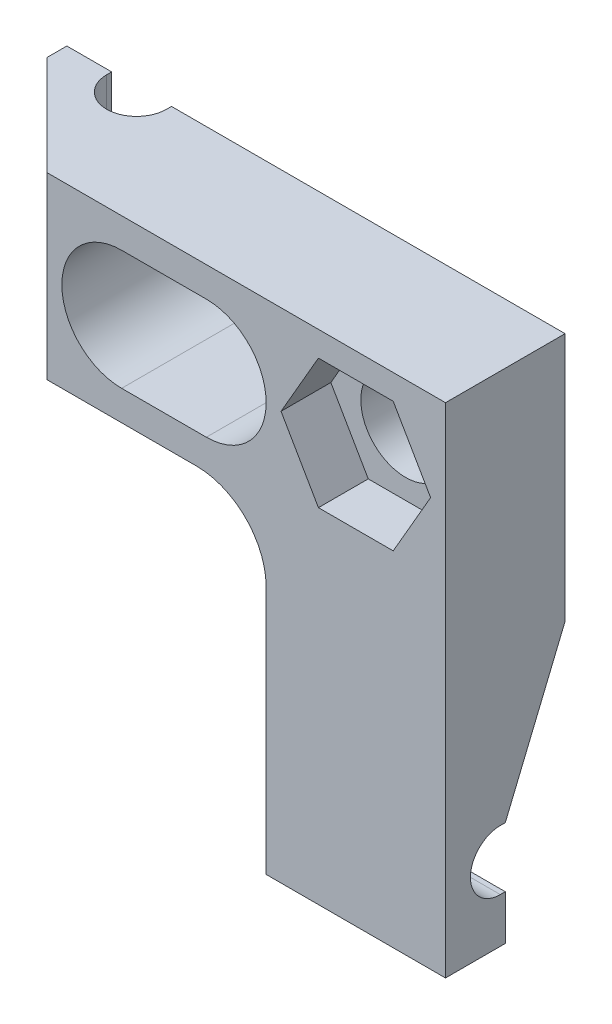
SolidWorks part; units mm, degrees
ref_plane "xy" through (0, 0, 0) normal (0, 0, 1) x (1, 0, 0)
ref_plane "xz" through (0, 0, 0) normal (0, 1, 0) x (1, 0, 0)
ref_plane "yz" through (0, 0, 0) normal (1, 0, 0) x (0, 0, -1)
sketch "Skizze1" plane through (0, 0, 0) normal (0, 0, 1) x (1, 0, 0)
  line L0 (0, 0) -> (-27.5, -27.5) construction
  line L1 (12.5, 54.5) -> (54.5, 12.5) construction
  line L2 (12.5, 54.5) -> (54.5, 54.5) construction
  line L3 (12.5, 54.5) -> (12.5, 12.5) construction
  line L4 (12.5, 12.5) -> (54.5, 12.5) construction
  line L5 (-7.5, -7.5) -> (-27.5, -7.5) construction
  line L6 (-7.5, -7.5) -> (-7.5, -27.5) construction
  line L7 (-7.5, -27.5) -> (-27.5, -27.5) construction
  line L8 (-27.5, -7.5) -> (-27.5, -27.5) construction
  line L9 (-27.5, -7.5) -> (-22.5, -7.5) construction
  line L10 (-27.5, -7.5) -> (-27.5, 7.5) construction
  line L11 (-27.5, 7.5) -> (-22.5, 7.5) construction
  line L12 (-22.5, -7.5) -> (-22.5, 7.5) construction
  line L13 (-27.5, 3) -> (55.808, 3) construction
  line L14 (-27.5, 3) -> (-27.5, -3) construction
  line L15 (-27.5, -3) -> (55.808, -3) construction
  line L16 (55.808, 3) -> (55.808, -3) construction
  line L17 (-7.5, -7.5) -> (12.5, -7.5) construction
  line L18 (12.5, -7.5) -> (12.5, -27.5) construction
  line L19 (12.5, -27.5) -> (-7.5, -27.5) construction
  line L20 (12.5, -17.5) -> (14.5, -17.5) construction
  line L21 (14.5, -10) -> (19.5, -10) construction
  line L22 (14.5, -10) -> (14.5, -25) construction
  line L23 (14.5, -25) -> (19.5, -25) construction
  line L24 (19.5, -10) -> (19.5, -25) construction
  line L25 (54.5, 54.5) -> (54.5, 12.5) construction
  line L27 (-3, -38.6322) -> (3, -38.6322) construction
  line L28 (-3, -38.6322) -> (-3, 55.6456) construction
  line L29 (-3, 55.6456) -> (3, 55.6456) construction
  line L30 (3, -38.6322) -> (3, 55.6456) construction
  line L31 (39.5, 36.9641) -> (33.5, 40.4282)
  line L32 (33.5, 40.4282) -> (27.5, 36.9641)
  line L33 (27.5, 36.9641) -> (27.5, 30.0359)
  line L34 (27.5, 30.0359) -> (33.5, 26.5718)
  line L35 (33.5, 26.5718) -> (39.5, 30.0359)
  line L36 (39.5, 30.0359) -> (39.5, 36.9641)
  circle A0 centre (33.5, 33.5) radius 6 construction
  point P18 (-27.5, 0)
  point P28 (17, -10)
  point P31 (33.5, 33.5)
  dimension "D1" = 42
  dimension "D2" = 20
  dimension "D3" = 5
  dimension "D4" = 15
  dimension "D5" = 6
  dimension "D6" = 2
  dimension "D7" = 20
  dimension "D8" = 20
  dimension "D9" = 4.5
  dimension "D10" = 12
sketch "Skizze2" plane through (0, 0, 0) normal (0, 0, 1) x (1, 0, 0)
  line L0 (-7.5, 42.5) -> (-7.5, 24.5)
  line L1 (-7.5, 24.5) -> (17.5, 24.5)
  line L2 (24.5, 17.5) -> (24.5, -7.5)
  line L3 (24.5, -7.5) -> (42.5, -7.5)
  line L4 (42.5, -7.5) -> (42.5, 42.5)
  line L5 (-7.5, 42.5) -> (42.5, 42.5)
  line L6 (-7.5, -7.5) -> (-7.5, -27.5) construction
  arc A0 (17.5, 24.5) -> (24.5, 17.5) centre (17.5, 17.5) cw
  circle A1 centre (33.5, 33.5) radius 4.5
  point P12 (33.5, -7.5)
  point P14 (-7.5, 33.5)
  dimension "D3" = 9
  dimension "D1" = 18
  dimension "D2" = 25
extrude "Aufsatz-Linear austragen1" add sketch "Skizze2" along normal blind 12
sketch "Skizze5" plane through (0, 0, 12) normal (0, 0, 1) x (1, 0, 0)
  line L0 (39.5, 36.9641) -> (39.1292, 36.75) construction
  line L1 (41.0056, 33.5) -> (37.2528, 40)
  line L2 (37.2528, 40) -> (29.7472, 40)
  line L3 (29.7472, 40) -> (25.9944, 33.5)
  line L4 (25.9944, 33.5) -> (29.7472, 27)
  line L5 (29.7472, 27) -> (37.2528, 27)
  line L6 (37.2528, 27) -> (41.0056, 33.5)
  circle A0 centre (33.5, 33.5) radius 6.5 construction
  dimension "D1" = 13
extrude "Schnitt-Linear austragen6" cut sketch "Skizze5" against normal blind 5
sketch "Skizze3" plane through (0, 0, 0) normal (0, 1, 0) x (1, 0, 0)
  line L0 (0, 4.577) -> (0, -0.5) construction
  line L1 (3, 4.577) -> (3, -0.5)
  line L2 (-3, 4.577) -> (-3, -0.5)
  line L3 (-45.8194, 0) -> (45.8194, 0) construction
  arc A0 (3, 4.577) -> (-3, 4.577) centre (0, 4.577) ccw
  arc A1 (-3, -0.5) -> (3, -0.5) centre (0, -0.5) ccw
  point P2 (0, 2.0385)
  dimension "D2" = 3
  dimension "D1" = 0.5
extrude "Schnitt-Linear austragen1" cut sketch "Skizze3" along normal through all
sketch "Skizze4" plane through (0, 0, 0) normal (1, 0, 0) x (0, 0, -1)
  line L0 (-0.5, 0) -> (-6.5, 0) construction
  line L1 (-0.5, -3) -> (-6.5, -3)
  line L2 (-0.5, 3) -> (-6.5, 3)
  line L3 (4.577, 0) -> (-0.5, 0) construction
  arc A0 (-0.5, -3) -> (-0.5, 3) centre (-0.5, 0) ccw
  arc A1 (-6.5, 3) -> (-6.5, -3) centre (-6.5, 0) ccw
  point P2 (-3.5, 0)
  dimension "D1" = 3
  dimension "D2" = 6
  dimension "D3" = 6
extrude "Schnitt-Linear austragen5" cut sketch "Skizze4" along normal through all
sketch "Skizze6" plane through (0, 0, 0) normal (0, 0, -1) x (-1, 0, 0)
  line L1 (-42.5, -7.5) -> (-24.5, -7.5)
  line L2 (-42.5, -7.5) -> (-42.5, 17.5)
  line L3 (-42.5, 17.5) -> (-24.5, 17.5)
  line L4 (-24.5, -7.5) -> (-24.5, 17.5)
extrude "Schnitt-Linear austragen7" cut sketch "Skizze6" against normal blind 6
sketch "Skizze7" plane through (42.5, 0, 0) normal (1, 0, 0) x (0, 0, -1)
  line L0 (-6, 3) -> (-6, 17.5)
  line L1 (-6, 17.5) -> (0, 17.5)
  line L2 (0, 17.5) -> (-6, 3)
extrude "Aufsatz-Linear austragen2" add sketch "Skizze7" against normal blind 3
sketch "Skizze8" plane through (24.5, 0, 0) normal (-1, 0, 0) x (0, 0, 1)
  line L0 (6, 3) -> (6, 17.5)
  line L1 (6, 17.5) -> (0, 17.5)
  line L2 (0, 17.5) -> (6, 3)
extrude "Aufsatz-Linear austragen3" add sketch "Skizze8" against normal blind 3
sketch "Skizze9" plane through (0, 0, 0) normal (0, 0, -1) x (-1, 0, 0)
  line L0 (-18.5, 33.5) -> (-10, 33.5) construction
  line L1 (-18.5, 39.5) -> (-10, 39.5)
  line L2 (-18.5, 27.5) -> (-10, 27.5)
  line L3 (-3, -38.6322) -> (-3, 55.6456) construction
  line L4 (-27.5, 36.9641) -> (-27.5, 30.0359) construction
  line L5 (-42.5, 42.5) -> (-3, 42.5) construction
  arc A0 (-18.5, 39.5) -> (-18.5, 27.5) centre (-18.5, 33.5) ccw
  arc A1 (-10, 27.5) -> (-10, 39.5) centre (-10, 33.5) ccw
  point P2 (-14.25, 33.5)
  dimension "D1" = 7
  dimension "D2" = 9
  dimension "D3" = 3
extrude "Schnitt-Linear austragen8" cut sketch "Skizze9" against normal through all
chamfer "Fase1" distance 10 angle 45 1 edges at (-7.5, 33.5, 12)
